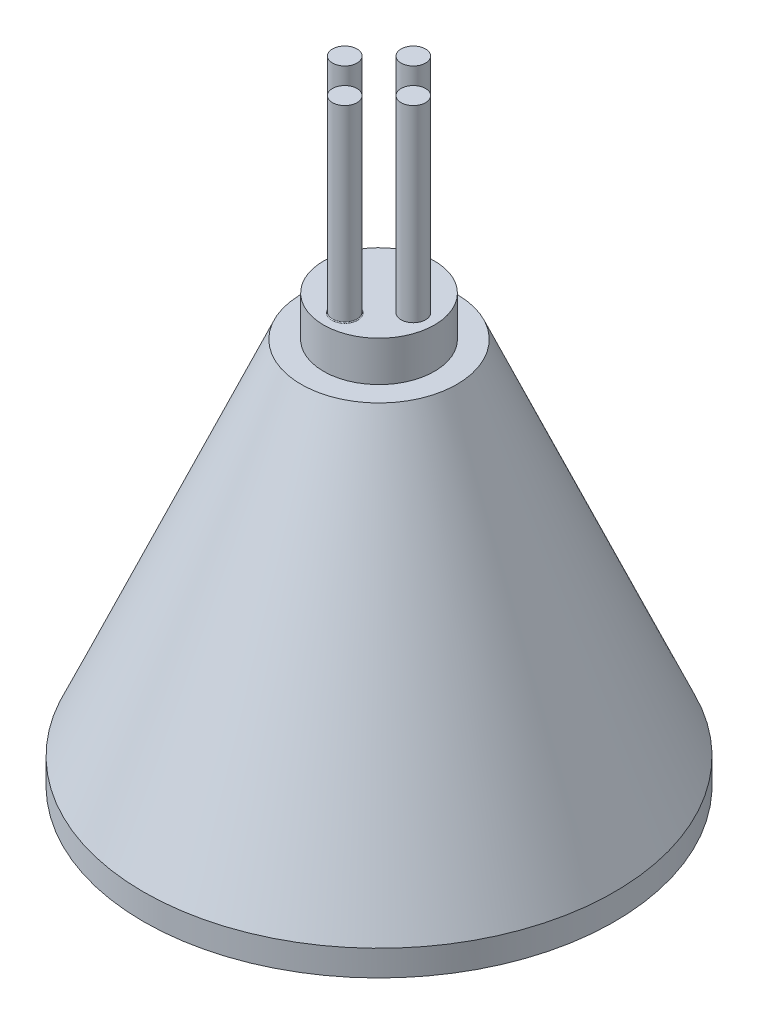
SolidWorks part; units mm, degrees
ref_plane "Front Plane" through (0, 0, 0) normal (0, 0, 1) x (1, 0, 0)
ref_plane "Top Plane" through (0, 0, 0) normal (0, 1, 0) x (1, 0, 0)
ref_plane "Right Plane" through (0, 0, 0) normal (1, 0, 0) x (0, 0, -1)
sketch "Sketch1" plane through (0, 0, 0) normal (1, 0, 0) x (0, 0, -1)
  line L0 (127, 271.5) -> (635, 271.5) construction
  line L1 (618.284, 10.9286) -> (618.284, 7.7783)
  line L2 (647.1285, 60.0528) -> (640.3357, 60.0528)
  line L3 (640.3357, 55.1305) -> (637.5793, 55.1305)
  line L4 (637.5793, 55.1305) -> (618.284, 10.9286)
  line L5 (618.284, 7.7783) -> (647.1285, 7.7783)
  line L6 (647.1285, 60.0528) -> (647.1285, 7.7783) construction
  line L7 (640.3357, 60.0528) -> (640.3357, 55.1305)
  line L8 (647.1285, 60.0528) -> (647.1285, 7.7783)
revolve "Revolve1" add sketch "Sketch1" angle 360 about L8
sketch "Sketch2" plane through (0, 60.0528, 0) normal (0, 1, 0) x (1, 0, 0)
  circle A4 centre (0, 651.3285) radius 1.5
  circle A5 centre (-4.2, 647.1285) radius 1.5
  circle A6 centre (0, 642.9285) radius 1.5
  circle A7 centre (4.2, 647.1285) radius 1.5
extrude "Boss-Extrude1" add sketch "Sketch2" along normal blind 23.04
fillet "Fillet1" radius 0.1 1 edges at (0, 60.0528, -641.4285)
